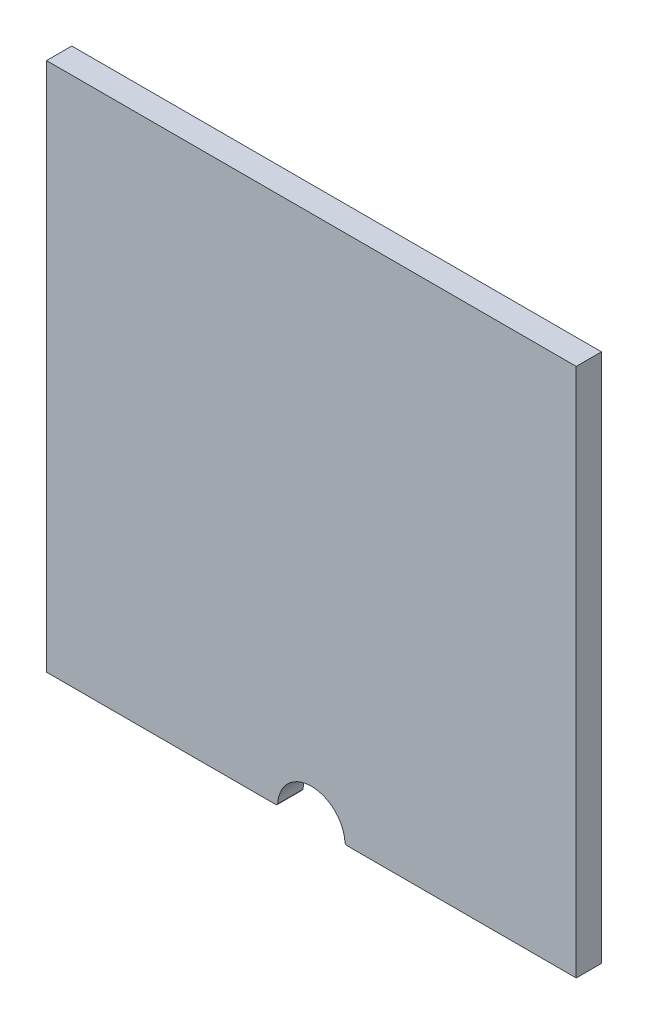
SolidWorks part; units mm, degrees
material "NEOPRENE"
ref_plane "Front Plane" through (0, 0, 0) normal (0, 0, 1) x (1, 0, 0)
ref_plane "Top Plane" through (0, 0, 0) normal (0, 1, 0) x (1, 0, 0)
ref_plane "Right Plane" through (0, 0, 0) normal (1, 0, 0) x (0, 0, -1)
sketch "Sketch1" plane through (0, 0, 0) normal (0, 0, 1) x (1, 0, 0)
  line L1 (0, 0) -> (200, 0)
  line L2 (0, 0) -> (0, 200)
  line L3 (0, 200) -> (200, 200)
  line L4 (200, 0) -> (200, 200)
  dimension "D1" = 200
extrude "Boss-Extrude1" add sketch "Sketch1" along normal blind 9.525
sketch "Sketch5" plane through (0, 0, 9.525) normal (0, 0, 1) x (1, 0, 0)
  line L0 (200, 0) -> (200, 200) construction
  line L1 (0, 0) -> (200, 0) construction
  line L2 (0, 200) -> (0, 0) construction
  line L3 (200, 200) -> (0, 200) construction
  line L4 (200, 0) -> (200, 200)
  line L5 (0, 0) -> (200, 0)
  line L6 (0, 200) -> (0, 0)
  line L7 (200, 200) -> (0, 200)
  line L8 (199.9492, 0.0508) -> (199.9492, 199.9492)
  line L9 (199.9492, 199.9492) -> (0.0508, 199.9492)
  line L10 (0.0508, 199.9492) -> (0.0508, 0.0508)
  line L11 (0.0508, 0.0508) -> (199.9492, 0.0508)
  dimension "D1" = 0.0508
extrude "Cut-Extrude2" cut sketch "Sketch5" against normal through all
sketch "Sketch2" plane through (0, 0, 9.525) normal (0, 0, 1) x (1, 0, 0)
  line L1 (87.3, 0.0508) -> (112.7, 0.0508)
  line L2 (0.0508, 0.0508) -> (199.9492, 0.0508) construction
  line L3 (100, 199.9492) -> (100, 0.0508) construction
  line L4 (199.9492, 199.9492) -> (0.0508, 199.9492) construction
  arc A0 (112.7, 0.0508) -> (87.3, 0.0508) centre (100, 0.0508) ccw
  dimension "D1" = 25.4
extrude "Cut-Extrude1" cut sketch "Sketch2" against normal blind 9.525
fillet "Fillet1" radius 0.7937 2 edges at (87.3, 0.0508, 4.7625) (112.7, 0.0508, 4.7625)
sketch "Sketch6" plane through (0, 0, 9.525) normal (0, 0, 1) x (1, 0, 0)
  line L0 (0.0508, 199.9492) -> (0.0508, 0.0508) construction
  line L1 (0.0508, 0.0508) -> (86.5296, 0.0508) construction
  circle A0 centre (2.0828, 2.0828) radius 0.7938
  dimension "D1" = 1.5875
  dimension "D2" = 2.032
  dimension "D3" = 2.032
extrude "Cut-Extrude3" [suppressed] cut sketch "Sketch6" against normal blind 1.27
pattern_linear "LPattern1" [suppressed] count 4 spacing 2.54
